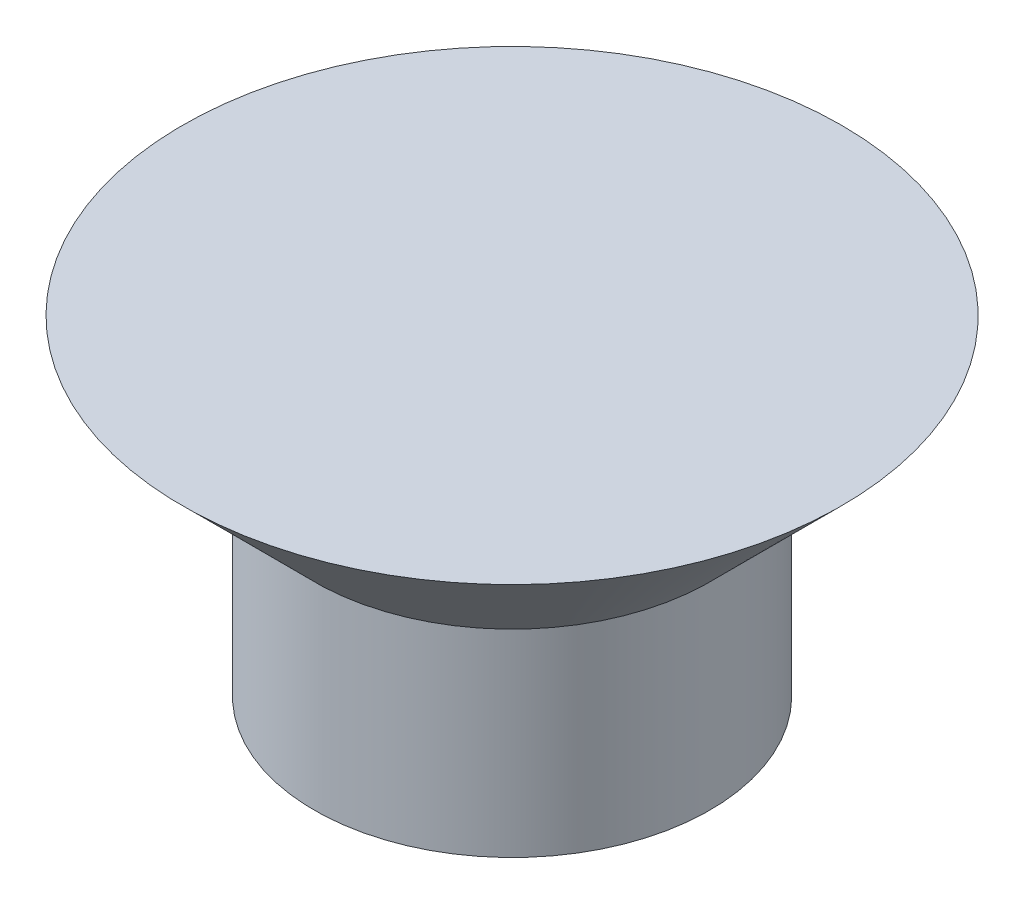
SolidWorks part; units mm, degrees
ref_plane "Front Plane" through (0, 0, 0) normal (0, 0, 1) x (1, 0, 0)
ref_plane "Top Plane" through (0, 0, 0) normal (0, 1, 0) x (1, 0, 0)
ref_plane "Right Plane" through (0, 0, 0) normal (1, 0, 0) x (0, 0, -1)
sketch "Sketch1" plane through (0, 0, 0) normal (0, 0, 1) x (1, 0, 0)
  line L0 (0, 0) -> (0, 2.5)
  line L1 (0, 2.5) -> (2.5, 2.5)
  line L2 (2.5, 2.5) -> (1.5, 1.5)
  line L3 (1.5, 1.5) -> (1.5, 0)
  line L4 (1.5, 0) -> (0, 0)
  dimension "D1" = 1.5
  dimension "D2" = 2.5
  dimension "D3" = 1.5
  dimension "D4" = 2.5
revolve "Revolve1" add sketch "Sketch1" angle 360 about L0
sketch "Orientation Sketch" plane through (0, 2.5, 0) normal (0, 1, 0) x (1, 0, 0)
  circle A0 centre (0, 0) radius 2.5 construction
  circle A1 centre (0, 0) radius 2.5
  point P3 (0, 0)
other "FormTool1"
